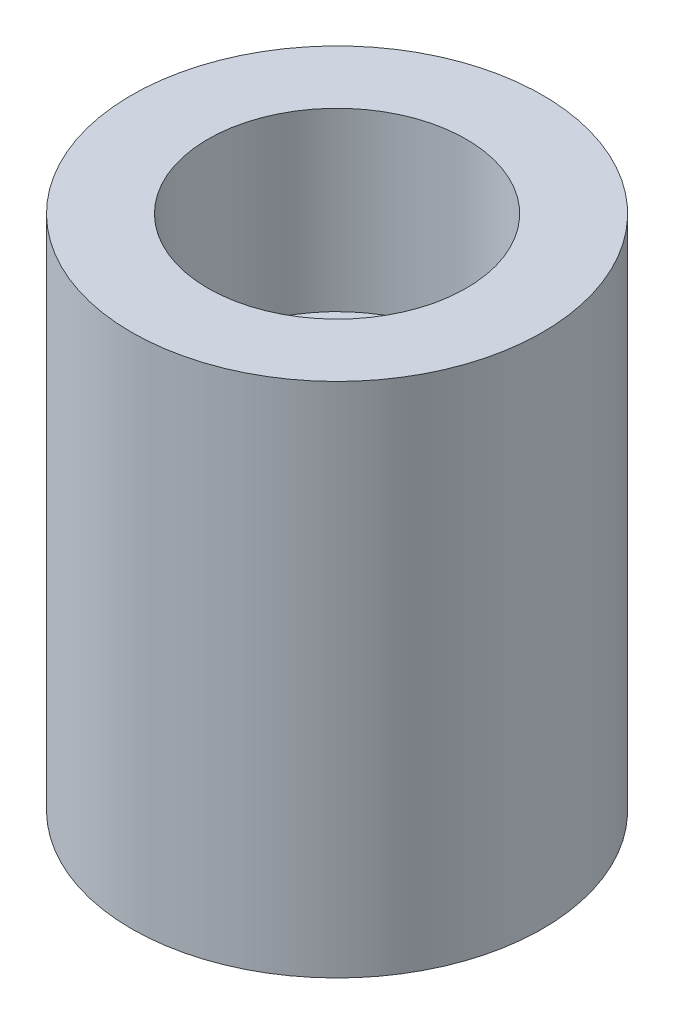
SolidWorks part; units mm, degrees
ref_plane "前视基准面" through (0, 0, 0) normal (0, 0, 1) x (1, 0, 0)
ref_plane "上视基准面" through (0, 0, 0) normal (0, 1, 0) x (1, 0, 0)
ref_plane "右视基准面" through (0, 0, 0) normal (1, 0, 0) x (0, 0, -1)
other "Configuration Table"
sketch "草图1" plane through (0, 0, 0) normal (0, 1, 0) x (1, 0, 0)
  circle A0 centre (0, 0) radius 1.75
  dimension "D1" = 3.5
extrude "凸台-拉伸1" add sketch "草图1" along normal blind 2.9
sketch "草图2" plane through (0, 2.9, 0) normal (0, 1, 0) x (1, 0, 0)
  circle A0 centre (0, 0) radius 1.75
  circle A1 centre (0, 0) radius 1.1
  dimension "D1" = 3.5
  dimension "D2" = 2.2
extrude "凸台-拉伸2" add sketch "草图2" along normal blind 1.5
